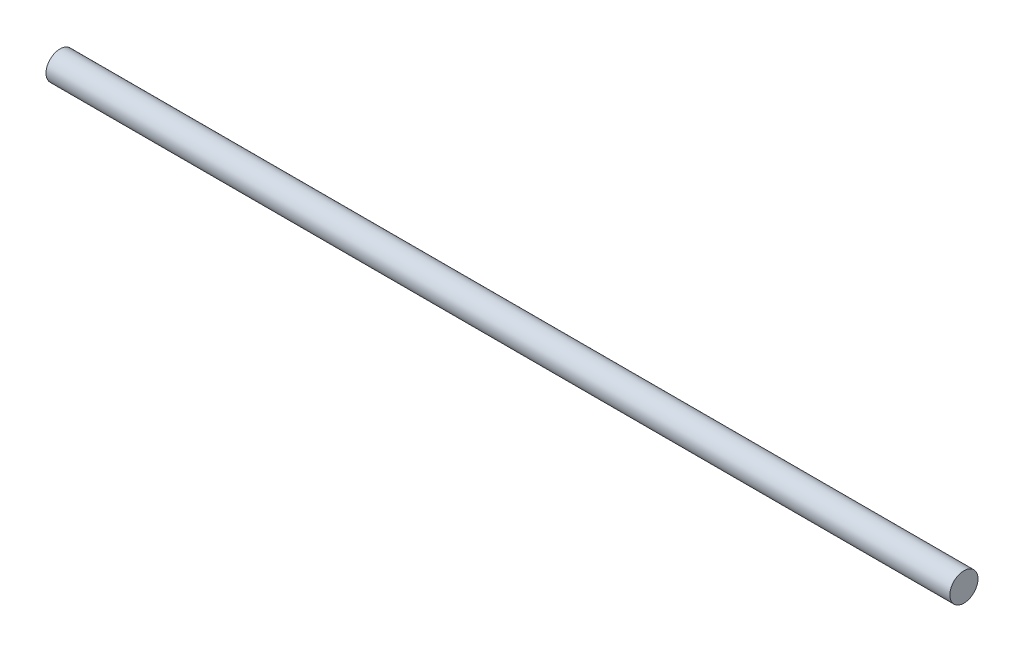
SolidWorks part; units mm, degrees
material "AISI 4340 Steel, annealed"
ref_plane "Front Plane" through (0, 0, 0) normal (0, 0, 1) x (1, 0, 0)
ref_plane "Top Plane" through (0, 0, 0) normal (0, 1, 0) x (1, 0, 0)
ref_plane "Right Plane" through (0, 0, 0) normal (1, 0, 0) x (0, 0, -1)
sketch "Sketch1" plane through (0, 0, 0) normal (1, 0, 0) x (0, 0, -1)
  circle A0 centre (0, 0) radius 5
  dimension "D1" = 10
extrude "Boss-Extrude1" add sketch "Sketch1" along normal mid plane 321 contours A0
